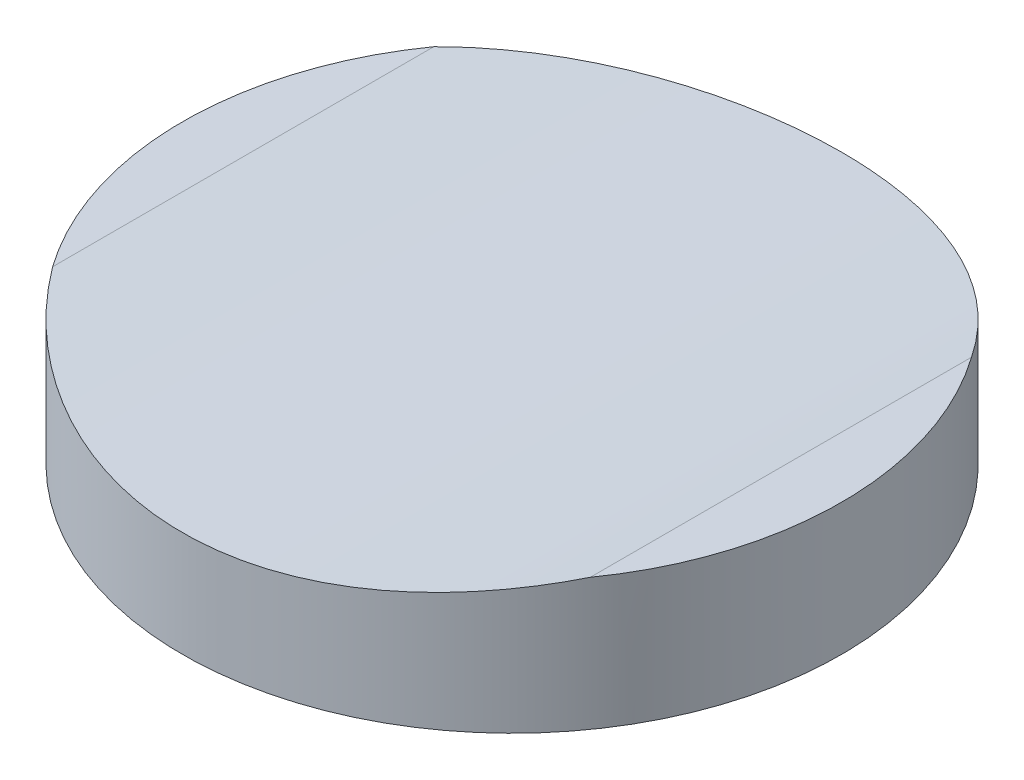
SolidWorks part; units mm, degrees
ref_plane "Front Plane" through (0, 0, 0) normal (0, 0, 1) x (1, 0, 0)
ref_plane "Top Plane" through (0, 0, 0) normal (0, 1, 0) x (1, 0, 0)
ref_plane "Right Plane" through (0, 0, 0) normal (1, 0, 0) x (0, 0, -1)
sketch "Sketch1" plane through (0, 0, 0) normal (0, 0, 1) x (1, 0, 0)
  line L0 (0, 0) -> (0, 10) construction
  line L1 (0, 10) -> (25, 10)
  line L2 (25, 10) -> (25, 0)
  line L3 (25, 0) -> (0, 0)
  line L4 (0, 0) -> (0, 10)
  dimension "D1" = 50
  dimension "D2" = 10
revolve "Revolve1" add sketch "Sketch1" angle 360 about L0
sketch "Sketch2" plane through (0, 0, 0) normal (0, 0, 1) x (1, 0, 0)
  line L0 (-25, 0) -> (25, 0) construction
  circle A0 centre (0, 113) radius 105
  point P2 (0, 0)
  point P4 (0, 0)
  point P5 (0, 8)
  dimension "D1" = 210
  dimension "D2" = 8
extrude "Cut-Extrude1" cut sketch "Sketch2" against normal through all both and the other way through all
hole_wizard "Ø3.0mm Dowel Hole1" positions "Sketch3" profile "Sketch4" hole size "Ø3.0" standard "ISO"
sketch "Sketch3" plane through (0, 0, 0) normal (0, -1, 0) x (-1, 0, 0)
  point P0 (17, 0)
  point P3 (0, 0)
  dimension "D1" = 17
sketch "Sketch4" plane through (-17, 0, 0) normal (1, 0, 0) x (0, 0, -1)
  line L0 (0, 0) -> (0, 6)
  line L1 (0, 6) -> (1.5, 6)
  line L2 (1.5, 6) -> (1.5, 0)
  line L5 (1.5, 0) -> (0, 0)
  line L10 (0, 6) -> (-1.5, 6) construction
  line L11 (0, -6.35) -> (0, 107.95) construction
  dimension "Hole Dia." = 3
  dimension "Hole Depth" = 6
  dimension "Drill Angle" = 180
